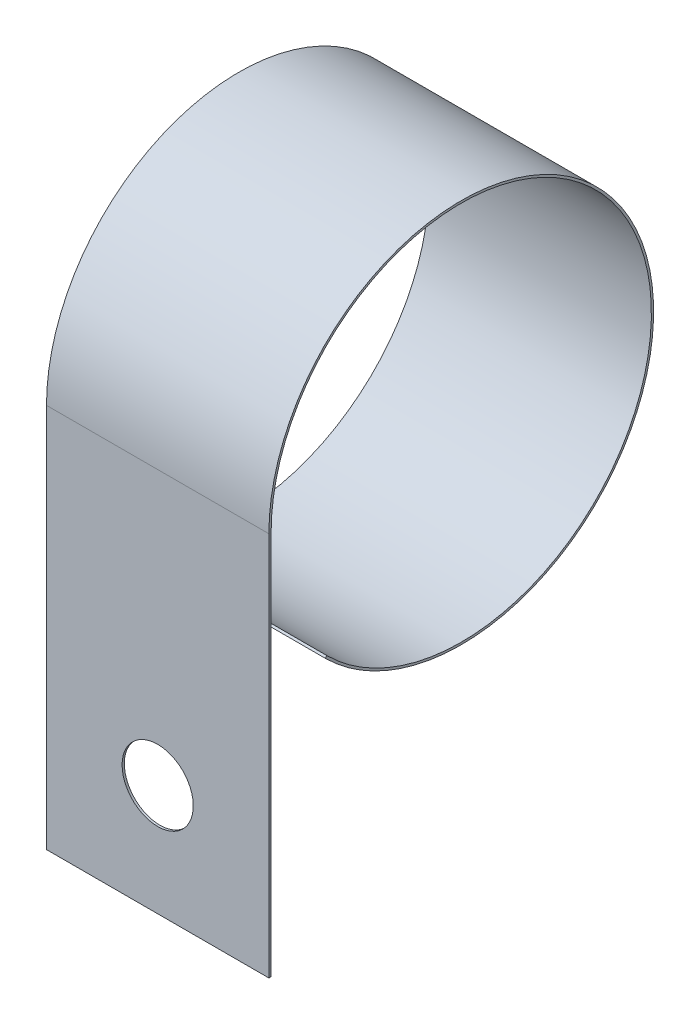
SolidWorks part; units mm, degrees
material "SUS304"
ref_plane "Front Plane" through (0, 0, 0) normal (0, 0, 1) x (1, 0, 0)
ref_plane "Top Plane" through (0, 0, 0) normal (0, 1, 0) x (1, 0, 0)
ref_plane "Right Plane" through (0, 0, 0) normal (1, 0, 0) x (0, 0, -1)
sketch "Sketch1" plane through (0, 0, 0) normal (1, 0, 0) x (0, -1, 0)
  line L7 (0, 0) -> (0, -8.55) construction
  line L8 (6.1165, -6.1165) -> (0, 0) construction
  line L9 (6.1165, -6.1165) -> (6.0458, -6.0458)
  line L10 (17.3, -8.65) -> (0, -8.65)
  line L11 (17.3, -8.55) -> (17.3, -8.65)
  line L12 (17.3, -8.55) -> (0, -8.55)
  circle A3 centre (0, 0) radius 8.55 construction
  arc A4 (0, -8.65) -> (6.1165, -6.1165) centre (0, 0) cw
  arc A5 (0, -8.55) -> (6.0458, -6.0458) centre (0, 0) cw
  dimension "MSM_1" = 17.1
  dimension "MSM_5" = 17.3
  dimension "FIX_1" = 45
  dimension "Accessories Plate Thickness" = 0.1
extrude "Boss-Extrude1" add sketch "Sketch1" along normal mid plane 10
sketch "Sketch2" plane through (0, 0, 8.65) normal (0, 0, -1) x (-1, 0, 0)
  circle A0 centre (0, -12.3) radius 1.6
  dimension "D_s" = 3.2
  dimension "Y" = 5
extrude "Cut-Extrude1" cut sketch "Sketch2" along normal up to next
